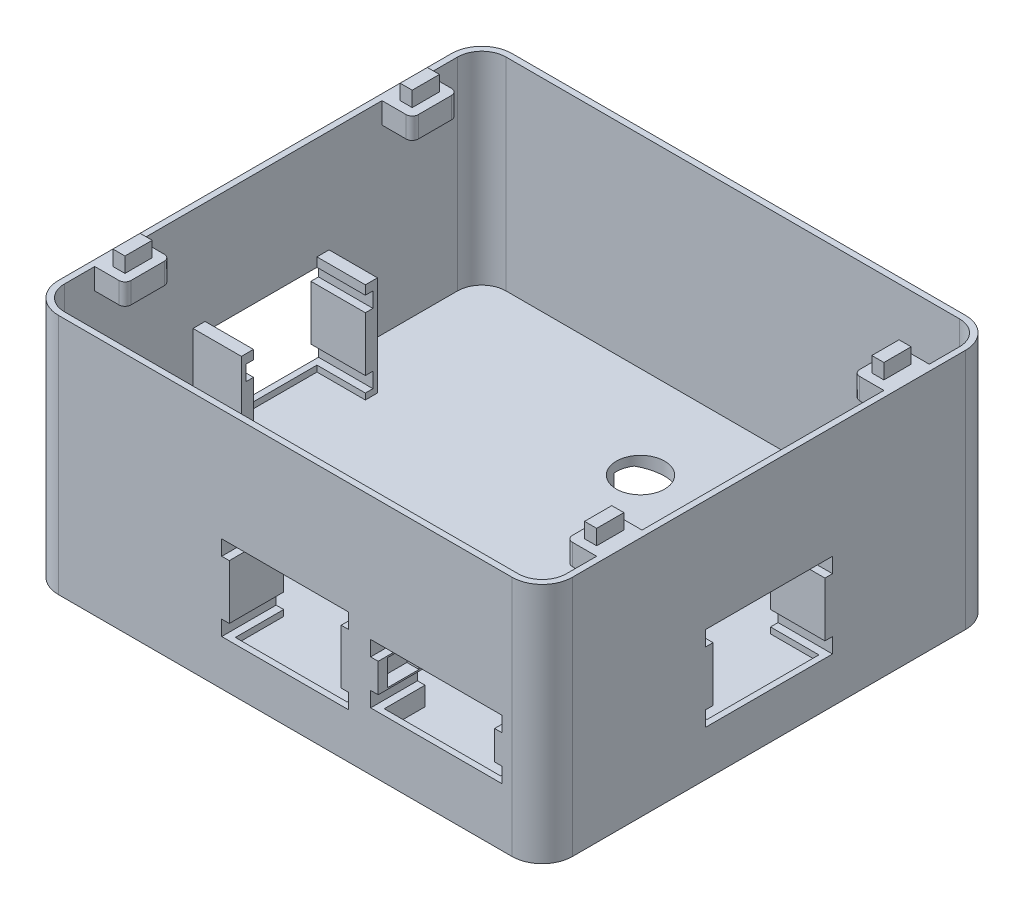
SolidWorks part; units mm, degrees
ref_plane "Front Plane" through (0, 0, 0) normal (0, 0, 1) x (1, 0, 0)
ref_plane "Top Plane" through (0, 0, 0) normal (0, 1, 0) x (1, 0, 0)
ref_plane "Right Plane" through (0, 0, 0) normal (1, 0, 0) x (0, 0, -1)
sketch "Sketch2" plane through (0, 0, 0) normal (0, 1, 0) x (1, 0, 0)
  line L1 (-85, 75) -> (85, 75)
  line L2 (-85, 75) -> (-85, -75)
  line L3 (-85, -75) -> (85, -75)
  line L4 (85, 75) -> (85, -75)
  line L5 (-85, 75) -> (85, -75) construction
  line L6 (-85, -75) -> (85, 75) construction
  point P0 (0, 0)
  dimension "D1" = 170
  dimension "D2" = 150
extrude "Boss-Extrude1" add sketch "Sketch2" along normal blind 80
fillet "Fillet1" radius 10 4 edges at (-85, 40, -75) (85, 40, -75) (85, 40, 75) (-85, 40, 75)
shell "Shell1" thickness 2
sketch "Sketch5" plane through (0, 0, 75) normal (0, 0, 1) x (1, 0, 0)
  line L1 (-18.5, 43) -> (18.5, 43)
  line L2 (-18.5, 43) -> (-18.5, 15)
  line L3 (-18.5, 15) -> (18.5, 15)
  line L4 (18.5, 43) -> (18.5, 15)
  line L5 (-18.5, 43) -> (-21, 43)
  line L6 (-21, 43) -> (-21, 38)
  line L7 (-21, 38) -> (-18.5, 38)
  line L8 (-18.5, 38) -> (-18.5, 43)
  line L9 (0, 43) -> (0, 15) construction
  line L10 (-18.5, 29) -> (18.5, 29) construction
  line L11 (-21, 20) -> (-18.5, 20)
  line L12 (-21, 15) -> (-21, 20)
  line L13 (-18.5, 15) -> (-21, 15)
  line L14 (-18.5, 20) -> (-18.5, 15)
  line L15 (21, 15) -> (21, 20)
  line L16 (18.5, 15) -> (21, 15)
  line L17 (18.5, 20) -> (18.5, 15)
  line L18 (21, 20) -> (18.5, 20)
  line L19 (21, 38) -> (18.5, 38)
  line L20 (21, 43) -> (21, 38)
  line L21 (18.5, 43) -> (21, 43)
  line L22 (18.5, 38) -> (18.5, 43)
  line L23 (-75, 13) -> (75, 13) construction
  point P4 (0, 15)
  dimension "D1" = 37
  dimension "D2" = 28
  dimension "D3" = 5
  dimension "D7" = 2.5
  dimension "D8" = 2
extrude "Cut-Extrude1" cut sketch "Sketch5" against normal up to surface (2 mm away) contours L1 L4 L3 L2 | L7 L8 L5 L6 | L12 L11 L14 L13 | L20 L19 L22 L21 | L15 L18 L17 L16 up to face at (0, 46.5, 73)
sketch "Sketch6" plane through (0, 0, 73) normal (0, 0, -1) x (-1, 0, 0)
  line L0 (18.5, 13) -> (22.5, 13)
  line L2 (-22.5, 46) -> (-22.5, 13)
  line L4 (21, 43) -> (18.5, 43)
  line L5 (21, 38) -> (21, 43)
  line L6 (18.5, 38) -> (21, 38)
  line L7 (18.5, 43) -> (18.5, 38)
  line L8 (21, 43) -> (18.5, 43)
  line L9 (21, 38) -> (21, 43)
  line L10 (18.5, 38) -> (21, 38)
  line L12 (18.5, 43) -> (-18.5, 43)
  line L13 (-18.5, 43) -> (-18.5, 15)
  line L14 (-18.5, 15) -> (18.5, 15)
  line L15 (18.5, 15) -> (18.5, 43)
  line L17 (-18.5, 46) -> (-18.5, 43)
  line L19 (18.5, 13) -> (18.5, 15)
  line L20 (-21, 38) -> (-18.5, 38)
  line L21 (-18.5, 38) -> (-18.5, 43)
  line L22 (-18.5, 43) -> (-21, 43)
  line L23 (-21, 43) -> (-21, 38)
  line L24 (-21, 38) -> (-18.5, 38)
  line L26 (-18.5, 43) -> (-21, 43)
  line L27 (-21, 43) -> (-21, 38)
  line L28 (-21, 20) -> (-21, 15)
  line L29 (-18.5, 20) -> (-21, 20)
  line L30 (-18.5, 15) -> (-18.5, 20)
  line L31 (-21, 15) -> (-18.5, 15)
  line L32 (-21, 20) -> (-21, 15)
  line L33 (-18.5, 20) -> (-21, 20)
  line L35 (-21, 15) -> (-18.5, 15)
  line L36 (21, 20) -> (18.5, 20)
  line L37 (18.5, 20) -> (18.5, 15)
  line L38 (18.5, 15) -> (21, 15)
  line L39 (21, 15) -> (21, 20)
  line L40 (21, 20) -> (18.5, 20)
  line L42 (18.5, 15) -> (21, 15)
  line L43 (21, 15) -> (21, 20)
  line L44 (22.5, 46) -> (22.5, 13)
  line L45 (-18.5, 13) -> (-22.5, 13)
  line L46 (-18.5, 38) -> (-18.5, 20)
  line L47 (18.5, 43) -> (18.5, 46)
  line L48 (18.5, 20) -> (18.5, 38)
  line L49 (-18.5, 15) -> (-18.5, 13)
  line L50 (22.5, 46) -> (18.5, 46)
  line L51 (-22.5, 46) -> (-18.5, 46)
  line L54 (21, 43) -> (-21, 43) construction
  line L55 (75, 13) -> (-75, 13) construction
  dimension "D6" = 3
  dimension "D7" = 4
  dimension "D8" = 4
  dimension "D1" = 0
  dimension "D2" = 0
  dimension "D3" = 0
  dimension "D4" = 0
  dimension "D5" = 0
extrude "Boss-Extrude2" add sketch "Sketch6" along normal blind 16
sketch "Sketch7" plane through (85, 0, 0) normal (1, 0, 0) x (0, 0, -1)
  line L0 (-65, 13) -> (65, 13) construction
  line L1 (-18.5, 43) -> (18.5, 43)
  line L2 (-18.5, 43) -> (-18.5, 15)
  line L3 (-18.5, 15) -> (18.5, 15)
  line L4 (18.5, 43) -> (18.5, 15)
  line L5 (-18.5, 43) -> (-21, 43)
  line L6 (-21, 43) -> (-21, 38)
  line L7 (-21, 38) -> (-18.5, 38)
  line L8 (-18.5, 38) -> (-18.5, 43)
  line L9 (0, 43) -> (0, 15) construction
  line L10 (-18.5, 29) -> (18.5, 29) construction
  line L11 (-21, 20) -> (-18.5, 20)
  line L12 (-21, 15) -> (-21, 20)
  line L13 (-18.5, 15) -> (-21, 15)
  line L14 (-18.5, 20) -> (-18.5, 15)
  line L15 (21, 15) -> (21, 20)
  line L16 (18.5, 15) -> (21, 15)
  line L17 (18.5, 20) -> (18.5, 15)
  line L18 (21, 20) -> (18.5, 20)
  line L19 (21, 38) -> (18.5, 38)
  line L20 (21, 43) -> (21, 38)
  line L21 (18.5, 43) -> (21, 43)
  line L22 (18.5, 38) -> (18.5, 43)
  dimension "D1" = 37
  dimension "D2" = 28
  dimension "D3" = 5
  dimension "D7" = 2.5
  dimension "D8" = 2
extrude "Cut-Extrude2" cut sketch "Sketch7" against normal blind 2 contours L1 L4 L3 L2 | L7 L8 L5 L6 | L12 L11 L14 L13 | L20 L19 L22 L21 | L15 L18 L17 L16
sketch "Sketch8" plane through (83, 0, 0) normal (-1, 0, 0) x (0, 0, 1)
  line L0 (65, 13) -> (-65, 13) construction
  line L1 (-22.5, 46) -> (-18.5, 46)
  line L2 (-22.5, 46) -> (-22.5, 13)
  line L3 (-22.5, 13) -> (-18.5, 13)
  line L4 (21, 43) -> (18.5, 43)
  line L5 (21, 38) -> (21, 43)
  line L6 (18.5, 38) -> (21, 38)
  line L7 (18.5, 43) -> (18.5, 38)
  line L8 (21, 43) -> (18.5, 43)
  line L9 (21, 38) -> (21, 43)
  line L10 (18.5, 38) -> (21, 38)
  line L20 (-21, 38) -> (-18.5, 38)
  line L21 (-18.5, 38) -> (-18.5, 43)
  line L22 (-18.5, 43) -> (-21, 43)
  line L23 (-21, 43) -> (-21, 38)
  line L24 (-21, 38) -> (-18.5, 38)
  line L26 (-18.5, 43) -> (-21, 43)
  line L27 (-21, 43) -> (-21, 38)
  line L28 (-21, 20) -> (-21, 15)
  line L29 (-18.5, 20) -> (-21, 20)
  line L30 (-18.5, 15) -> (-18.5, 20)
  line L31 (-21, 15) -> (-18.5, 15)
  line L32 (-21, 20) -> (-21, 15)
  line L33 (-18.5, 20) -> (-21, 20)
  line L35 (-21, 15) -> (-18.5, 15)
  line L36 (21, 20) -> (18.5, 20)
  line L37 (18.5, 20) -> (18.5, 15)
  line L38 (18.5, 15) -> (21, 15)
  line L39 (21, 15) -> (21, 20)
  line L40 (21, 20) -> (18.5, 20)
  line L42 (18.5, 15) -> (21, 15)
  line L43 (21, 15) -> (21, 20)
  line L44 (-18.5, 46) -> (-18.5, 43)
  line L46 (-18.5, 38) -> (-18.5, 20) construction
  line L47 (21, 43) -> (-21, 43) construction
  line L48 (-18.5, 38) -> (-18.5, 20)
  line L49 (-18.5, 15) -> (-18.5, 13)
  line L50 (18.5, 38) -> (18.5, 20) construction
  line L51 (18.5, 46) -> (22.5, 46)
  line L52 (18.5, 46) -> (18.5, 43)
  line L53 (18.5, 13) -> (22.5, 13)
  line L54 (22.5, 46) -> (22.5, 13)
  line L55 (18.5, 38) -> (18.5, 20)
  line L56 (18.5, 15) -> (18.5, 13)
  dimension "D6" = 4
  dimension "D7" = 4
  dimension "D2" = 3
  dimension "D1" = 0
  dimension "D3" = 0
  dimension "D4" = 0
  dimension "D5" = 0
extrude "Boss-Extrude3" add sketch "Sketch8" along normal blind 16
sketch "Sketch10" plane through (-85, 0, 0) normal (-1, 0, 0) x (0, 0, 1)
  line L1 (-18.5, 43) -> (18.5, 43)
  line L2 (-18.5, 43) -> (-18.5, 15)
  line L3 (-18.5, 15) -> (18.5, 15)
  line L4 (18.5, 43) -> (18.5, 15)
  line L5 (-18.5, 43) -> (-21, 43)
  line L6 (-21, 43) -> (-21, 38)
  line L7 (-21, 38) -> (-18.5, 38)
  line L8 (-18.5, 38) -> (-18.5, 43)
  line L9 (0, 43) -> (0, 15) construction
  line L10 (-18.5, 29) -> (18.5, 29) construction
  line L11 (-21, 20) -> (-18.5, 20)
  line L12 (-21, 15) -> (-21, 20)
  line L13 (-18.5, 15) -> (-21, 15)
  line L14 (-18.5, 20) -> (-18.5, 15)
  line L15 (21, 15) -> (21, 20)
  line L16 (18.5, 15) -> (21, 15)
  line L17 (18.5, 20) -> (18.5, 15)
  line L18 (21, 20) -> (18.5, 20)
  line L19 (21, 38) -> (18.5, 38)
  line L20 (21, 43) -> (21, 38)
  line L21 (18.5, 43) -> (21, 43)
  line L22 (18.5, 38) -> (18.5, 43)
  line L23 (-65, 13) -> (65, 13) construction
  dimension "D1" = 37
  dimension "D2" = 28
  dimension "D3" = 5
  dimension "D7" = 2.5
  dimension "D8" = 2
extrude "Cut-Extrude4" cut sketch "Sketch10" against normal blind 2 contours L1 L4 L3 L2 | L7 L8 L5 L6 | L12 L11 L14 L13 | L20 L19 L22 L21 | L15 L18 L17 L16
sketch "Sketch11" plane through (-83, 0, 0) normal (1, 0, 0) x (0, 0, -1)
  line L1 (-18.5, 38) -> (-18.5, 20) construction
  line L2 (-18.5, 46) -> (-22.5, 46)
  line L3 (-18.5, 46) -> (-18.5, 43)
  line L4 (21, 43) -> (18.5, 43)
  line L5 (21, 38) -> (21, 43)
  line L6 (18.5, 38) -> (21, 38)
  line L7 (18.5, 43) -> (18.5, 38)
  line L8 (21, 43) -> (18.5, 43)
  line L9 (21, 38) -> (21, 43)
  line L10 (18.5, 38) -> (21, 38)
  line L20 (-21, 38) -> (-18.5, 38)
  line L21 (-18.5, 38) -> (-18.5, 43)
  line L22 (-18.5, 43) -> (-21, 43)
  line L23 (-21, 43) -> (-21, 38)
  line L24 (-21, 38) -> (-18.5, 38)
  line L26 (-18.5, 43) -> (-21, 43)
  line L27 (-21, 43) -> (-21, 38)
  line L28 (-21, 20) -> (-21, 15)
  line L29 (-18.5, 20) -> (-21, 20)
  line L30 (-18.5, 15) -> (-18.5, 20)
  line L31 (-21, 15) -> (-18.5, 15)
  line L32 (-21, 20) -> (-21, 15)
  line L33 (-18.5, 20) -> (-21, 20)
  line L35 (-21, 15) -> (-18.5, 15)
  line L36 (21, 20) -> (18.5, 20)
  line L37 (18.5, 20) -> (18.5, 15)
  line L38 (18.5, 15) -> (21, 15)
  line L39 (21, 15) -> (21, 20)
  line L40 (21, 20) -> (18.5, 20)
  line L42 (18.5, 15) -> (21, 15)
  line L43 (21, 15) -> (21, 20)
  line L44 (-18.5, 13) -> (-22.5, 13)
  line L45 (-22.5, 46) -> (-22.5, 13)
  line L46 (65, 13) -> (-65, 13) construction
  line L47 (21, 43) -> (-21, 43) construction
  line L48 (-18.5, 38) -> (-18.5, 20)
  line L49 (-18.5, 15) -> (-18.5, 13)
  line L50 (18.5, 38) -> (18.5, 20) construction
  line L51 (18.5, 46) -> (22.5, 46)
  line L52 (18.5, 46) -> (18.5, 43)
  line L53 (18.5, 13) -> (22.5, 13)
  line L54 (22.5, 46) -> (22.5, 13)
  line L55 (18.5, 38) -> (18.5, 20)
  line L56 (18.5, 15) -> (18.5, 13)
  dimension "D2" = 4
  dimension "D6" = 3
  dimension "D7" = 4
  dimension "D1" = 0
  dimension "D3" = 0
  dimension "D4" = 0
  dimension "D5" = 0
extrude "Boss-Extrude4" add sketch "Sketch11" along normal blind 16
sketch "Sketch13" plane through (0, 0, 75) normal (0, 0, 1) x (1, 0, 0)
  line L0 (-18.5, 29) -> (18.5, 29) construction
  line L1 (-18.5, 29) -> (18.5, 29) construction
  line L2 (30.75, 38.8) -> (28.25, 38.8)
  line L3 (30.75, 38.8) -> (69.25, 38.8)
  line L4 (30.75, 38.8) -> (30.75, 19.2)
  line L5 (30.75, 19.2) -> (69.25, 19.2)
  line L6 (69.25, 38.8) -> (69.25, 19.2)
  line L7 (28.25, 38.8) -> (28.25, 33.8)
  line L8 (28.25, 33.8) -> (30.75, 33.8)
  line L9 (30.75, 38.8) -> (30.75, 33.8)
  line L10 (50, 38.8) -> (50, 19.2) construction
  line L11 (30.75, 19.2) -> (28.25, 19.2)
  line L12 (28.25, 19.2) -> (28.25, 24.2)
  line L13 (28.25, 24.2) -> (30.75, 24.2)
  line L14 (30.75, 19.2) -> (30.75, 24.2)
  line L15 (69.25, 19.2) -> (69.25, 24.2)
  line L16 (71.75, 24.2) -> (69.25, 24.2)
  line L17 (71.75, 19.2) -> (71.75, 24.2)
  line L18 (69.25, 19.2) -> (71.75, 19.2)
  line L19 (69.25, 38.8) -> (71.75, 38.8)
  line L20 (71.75, 38.8) -> (71.75, 33.8)
  line L21 (71.75, 33.8) -> (69.25, 33.8)
  line L22 (69.25, 38.8) -> (69.25, 33.8)
  point P6 (30.75, 29)
  point P7 (50, 19.2)
  dimension "D1" = 19.6
  dimension "D2" = 38.5
  dimension "D3" = 50
  dimension "D4" = 5
  dimension "D8" = 2.5
extrude "Cut-Extrude5" cut sketch "Sketch13" against normal up to surface (2 mm away) contours L3 L6 L5 L4 | L7 L8 L9 L2 | L12 L13 L14 L11 | L17 L16 L15 L18 | L20 L21 L22 L19 up to face at (0, 40.1667, 73)
sketch "Sketch14" plane through (0, 0, 73) normal (0, 0, -1) x (-1, 0, 0)
  line L0 (-22.5, 13) -> (-75, 13) construction
  line L1 (-69.25, 41.8) -> (-73.25, 41.8)
  line L2 (-69.25, 41.8) -> (-69.25, 38.8)
  line L3 (-69.25, 13) -> (-73.25, 13)
  line L6 (-73.25, 41.8) -> (-73.25, 13)
  line L12 (-28.25, 38.8) -> (-30.75, 38.8)
  line L13 (-28.25, 33.8) -> (-28.25, 38.8)
  line L14 (-30.75, 33.8) -> (-28.25, 33.8)
  line L15 (-30.75, 38.8) -> (-30.75, 33.8)
  line L16 (-28.25, 38.8) -> (-30.75, 38.8)
  line L17 (-28.25, 33.8) -> (-28.25, 38.8)
  line L18 (-30.75, 33.8) -> (-28.25, 33.8)
  line L20 (-69.25, 38.8) -> (-71.75, 38.8)
  line L21 (-71.75, 38.8) -> (-71.75, 33.8)
  line L22 (-71.75, 33.8) -> (-69.25, 33.8)
  line L23 (-69.25, 33.8) -> (-69.25, 38.8)
  line L24 (-69.25, 38.8) -> (-71.75, 38.8)
  line L25 (-71.75, 38.8) -> (-71.75, 33.8)
  line L26 (-71.75, 33.8) -> (-69.25, 33.8)
  line L28 (-69.25, 19.2) -> (-69.25, 24.2)
  line L29 (-69.25, 24.2) -> (-71.75, 24.2)
  line L30 (-71.75, 24.2) -> (-71.75, 19.2)
  line L31 (-71.75, 19.2) -> (-69.25, 19.2)
  line L33 (-69.25, 24.2) -> (-71.75, 24.2)
  line L34 (-71.75, 24.2) -> (-71.75, 19.2)
  line L35 (-71.75, 19.2) -> (-69.25, 19.2)
  line L36 (-28.25, 19.2) -> (-28.25, 24.2)
  line L37 (-28.25, 24.2) -> (-30.75, 24.2)
  line L38 (-30.75, 24.2) -> (-30.75, 19.2)
  line L39 (-30.75, 19.2) -> (-28.25, 19.2)
  line L40 (-28.25, 19.2) -> (-28.25, 24.2)
  line L41 (-28.25, 24.2) -> (-30.75, 24.2)
  line L43 (-30.75, 19.2) -> (-28.25, 19.2)
  line L44 (-28.25, 38.8) -> (-71.75, 38.8) construction
  line L45 (-30.75, 41.8) -> (-26.75, 41.8)
  line L46 (-30.75, 41.8) -> (-30.75, 38.8)
  line L47 (-30.75, 13) -> (-26.75, 13)
  line L48 (-26.75, 41.8) -> (-26.75, 13)
  line L49 (-69.25, 33.8) -> (-69.25, 24.2) construction
  line L50 (-30.75, 33.8) -> (-30.75, 24.2) construction
  line L51 (-69.25, 33.8) -> (-69.25, 24.2)
  line L52 (-69.25, 19.2) -> (-69.25, 13)
  line L53 (-30.75, 33.8) -> (-30.75, 24.2)
  line L54 (-30.75, 19.2) -> (-30.75, 13)
  dimension "D1" = 3
  dimension "D6" = 4
  dimension "D7" = 4
  dimension "D2" = 0
  dimension "D3" = 0
  dimension "D4" = 0
  dimension "D5" = 0
extrude "Boss-Extrude5" add sketch "Sketch14" along normal blind 13.5
sketch "Sketch15" plane through (26.75, 0, 0) normal (-1, 0, 0) x (0, 0, 1)
  line L4 (59.5, 13) -> (59.5, 41.8) construction
  line L5 (73, 13) -> (73, 41.8) construction
  line L6 (59.5, 41.8) -> (59.5, 13) construction
  line L7 (59.5, 33.8) -> (75, 33.8) construction
  line L8 (59.5, 24.2) -> (75, 24.2) construction
  line L12 (72, 24.7) -> (72, 33.3)
  line L13 (72, 33.3) -> (61.5, 33.3)
  line L14 (61.5, 33.3) -> (61.5, 24.7)
  line L15 (61.5, 24.7) -> (72, 24.7)
  dimension "D1" = 2
  dimension "D2" = 1
  dimension "D3" = 0.5
  dimension "D4" = 0.5
extrude "Cut-Extrude6" cut sketch "Sketch15" against normal up to surface (4 mm away) up to face at (30.75, 29, 67.25)
sketch "Sketch18" plane through (0, 0, 0) normal (1, 0, 0) x (0, 0, -1)
  line L0 (0, 0) -> (0, 10) construction
  line L2 (-22.5, 13) -> (-65, 13) construction
  line L3 (-42.5, 0) -> (-70, 0)
  line L4 (-70, 0) -> (-47.5, 10)
  line L5 (-47.5, 10) -> (-42.5, 10)
  line L6 (-42.5, 10) -> (-42.5, 0)
  line L7 (65, 0) -> (-65, 0) construction
  dimension "D1" = 3
  dimension "D2" = 70
  dimension "D3" = 5
  dimension "D4" = 42.5
revolve "Cut-Revolve1" cut sketch "Sketch18" angle 360 about L0
sketch "Sketch20" plane through (0, 0, 0) normal (0, -1, 0) x (1, 0, 0)
  circle A0 centre (0, -42.5) radius 8
  circle A1 centre (0, 0) radius 42.5 construction
  circle A2 centre (0, 0) radius 42.5 construction
  dimension "D1" = 16
extrude "Cut-Extrude8" cut sketch "Sketch20" against normal up to surface (13 mm away) up to face at (10, 13, 26.25)
sketch "Sketch22" plane through (0, 0, 0) normal (0, -1, 0) x (1, 0, 0)
  line L0 (-85, 65) -> (85, 65) construction
  line L1 (-82.0711, 72.0711) -> (-67.9289, 57.9289) construction
  line L2 (44, 0) -> (-44, 0) construction
  line L3 (0, -44) -> (0, 44) construction
  circle A0 centre (-67.9289, 57.9289) radius 3
  arc A5 (-75, 75) -> (-85, 65) centre (-75, 65) ccw construction
  circle A6 centre (-67.9289, -57.9289) radius 3
  circle A7 centre (67.9289, -57.9289) radius 3
  circle A8 centre (67.9289, 57.9289) radius 3
  dimension "D3" = 6
  dimension "D1" = 45
  dimension "D2" = 20
extrude "Cut-Extrude9" cut sketch "Sketch22" against normal blind 5
sketch "Sketch23" plane through (0, 13, 0) normal (0, 1, 0) x (1, 0, 0)
  line L0 (-83, 65) -> (-83, 22.5) construction
  line L1 (-83, 55) -> (-73, 55)
  line L2 (-83, 55) -> (-83, 40)
  line L3 (-83, 40) -> (-73, 40)
  line L4 (-73, 55) -> (-73, 40)
  dimension "D1" = 10
  dimension "D2" = 15
  dimension "D3" = 40
extrude "Boss-Extrude6" add sketch "Sketch23" along normal up to surface (7 mm away) from offset 60 up to face at (0, 80, 0)
sketch "Sketch24" plane through (0, 80, 0) normal (0, 1, 0) x (1, 0, 0)
  line L8 (-76, 52) -> (-80, 52)
  line L9 (-76, 43) -> (-76, 52)
  line L10 (-80, 43) -> (-76, 43)
  line L11 (-80, 52) -> (-80, 43)
  line L12 (-76, 52) -> (-80, 52)
  line L13 (-76, 43) -> (-76, 52)
  line L14 (-80, 43) -> (-76, 43)
  line L15 (-80, 52) -> (-80, 43)
  dimension "D1" = 3
extrude "Cut-Extrude10" cut sketch "Sketch24" against normal blind 5
mirror "Mirror1" about plane through (0, 0, 0) normal (1, 0, 0) of "Boss-Extrude6", "Cut-Extrude10" second plane through (0, 0, 0) second plane normal (0, 0, 1)
fillet "Fillet2" radius 2 8 edges at (-73, 76.5, -40) (-73, 76.5, -55) (-73, 76.5, 40) (-73, 76.5, 55) (73, 76.5, -40) (73, 76.5, -55) (73, 76.5, 40) (73, 76.5, 55)
sketch "Sketch25" plane through (0, 0, 75) normal (0, 0, 1) x (1, 0, 0)
  line L0 (-69, 74) -> (-69, 19)
  line L1 (-69, 19) -> (-33.5, 19)
  line L2 (-33.5, 19) -> (-33.5, 74)
  line L3 (-27.5, 49) -> (27.5, 49)
  line L4 (27.5, 49) -> (27.5, 74)
  line L5 (27.5, 74) -> (-27.5, 74)
  line L6 (-33.5, 74) -> (-69, 74)
  line L7 (33.5, 49) -> (69, 49)
  line L8 (69, 49) -> (69, 74)
  line L9 (69, 74) -> (33.5, 74)
  line L10 (33.5, 74) -> (33.5, 49)
  line L11 (-27.5, 74) -> (-27.5, 49)
  line L12 (-75, 80) -> (75, 80) construction
  line L13 (-21, 43) -> (21, 43) construction
  line L14 (75, 0) -> (75, 80) construction
  line L15 (-75, 80) -> (-75, 0) construction
  line L17 (-75, 13) -> (-22.5, 13) construction
  point P4 (0, 49)
  dimension "D1" = 6
  dimension "D2" = 6
  dimension "D3" = 6
  dimension "D4" = 6
  dimension "D5" = 6
  dimension "D6" = 6
  dimension "D7" = 6
  dimension "D8" = 55
sketch "Sketch26" plane through (83, 0, 0) normal (-1, 0, 0) x (0, 0, 1)
  line L0 (-37, 19) -> (-25.5, 19)
  line L1 (-25.5, 19) -> (-25.5, 74)
  line L2 (-25.5, 74) -> (-37, 74)
  line L3 (-37, 74) -> (-37, 19)
  line L4 (-19.5, 74) -> (-19.5, 52)
  line L5 (-19.5, 52) -> (19.5, 52)
  line L6 (19.5, 52) -> (19.5, 74)
  line L7 (19.5, 74) -> (-19.5, 74)
  line L8 (25.5, 74) -> (25.5, 19)
  line L9 (25.5, 19) -> (37, 19)
  line L10 (37, 19) -> (37, 74)
  line L11 (37, 74) -> (25.5, 74)
  line L12 (-22.5, 13) -> (-65, 13) construction
  line L15 (-22.5, 46) -> (-22.5, 13) construction
  line L18 (-18.5, 46) -> (-22.5, 46) construction
  line L19 (40, 80) -> (-40, 80) construction
  line L20 (-40, 80) -> (-40, 73) construction
  line L21 (40, 80) -> (40, 73) construction
  line L23 (-59, 67) -> (-43, 67)
  line L24 (-59, 67) -> (-59, 19)
  line L25 (-59, 19) -> (-43, 19)
  line L26 (-43, 67) -> (-43, 19)
  line L27 (43, 67) -> (59, 67)
  line L28 (43, 67) -> (43, 19)
  line L29 (43, 19) -> (59, 19)
  line L30 (59, 67) -> (59, 19)
  line L31 (-65, 13) -> (-65, 80) construction
  line L32 (55, 73) -> (40, 73) construction
  line L33 (65, 80) -> (65, 13) construction
  line L34 (-55, 73) -> (-40, 73) construction
  point P16 (0, 52)
  dimension "D1" = 6
  dimension "D2" = 6
  dimension "D3" = 6
  dimension "D4" = 6
  dimension "D5" = 3
  dimension "D6" = 3
  dimension "D7" = 3
  dimension "D8" = 6
  dimension "D9" = 6
  dimension "D10" = 6
  dimension "D11" = 6
  dimension "D12" = 6
  dimension "D13" = 6
  dimension "D14" = 6
sketch "Sketch29" plane through (-85, 0, 0) normal (-1, 0, 0) x (0, 0, 1)
  line L4 (25.5, 74) -> (25.5, 19)
  line L5 (25.5, 19) -> (37, 19)
  line L6 (37, 19) -> (37, 74)
  line L7 (37, 74) -> (25.5, 74)
  line L8 (25.5, 74) -> (25.5, 19)
  line L9 (25.5, 19) -> (37, 19)
  line L10 (37, 19) -> (37, 74)
  line L11 (37, 74) -> (25.5, 74)
  line L12 (-19.5, 74) -> (-19.5, 52)
  line L13 (-19.5, 52) -> (19.5, 52)
  line L14 (19.5, 52) -> (19.5, 74)
  line L15 (19.5, 74) -> (-19.5, 74)
  line L16 (-19.5, 74) -> (-19.5, 52)
  line L17 (-19.5, 52) -> (19.5, 52)
  line L18 (19.5, 52) -> (19.5, 74)
  line L19 (19.5, 74) -> (-19.5, 74)
  line L20 (-37, 19) -> (-25.5, 19)
  line L21 (-25.5, 19) -> (-25.5, 74)
  line L22 (-25.5, 74) -> (-37, 74)
  line L23 (-37, 74) -> (-37, 19)
  line L24 (-37, 19) -> (-25.5, 19)
  line L25 (-25.5, 19) -> (-25.5, 74)
  line L26 (-25.5, 74) -> (-37, 74)
  line L27 (-37, 74) -> (-37, 19)
  line L28 (-43, 67) -> (-59, 67)
  line L29 (-43, 19) -> (-43, 67)
  line L30 (-59, 19) -> (-43, 19)
  line L31 (-59, 67) -> (-59, 19)
  line L32 (-43, 67) -> (-59, 67)
  line L33 (-43, 19) -> (-43, 67)
  line L34 (-59, 19) -> (-43, 19)
  line L35 (-59, 67) -> (-59, 19)
  line L36 (59, 67) -> (43, 67)
  line L37 (43, 67) -> (43, 19)
  line L38 (43, 19) -> (59, 19)
  line L39 (59, 19) -> (59, 67)
  line L40 (59, 67) -> (43, 67)
  line L41 (43, 67) -> (43, 19)
  line L42 (43, 19) -> (59, 19)
  line L43 (59, 19) -> (59, 67)
  dimension "D1" = 0
  dimension "D2" = 0
  dimension "D3" = 0
  dimension "D4" = 0
  dimension "D5" = 0
sketch "Sketch27" plane through (0, 0, -75) normal (0, 0, -1) x (-1, 0, 0)
  line L0 (75, 0) -> (75, 80) construction
  line L1 (-69, 74) -> (-41, 74)
  line L2 (-69, 74) -> (-69, 19)
  line L3 (-69, 19) -> (-41, 19)
  line L4 (-41, 74) -> (-41, 19)
  line L5 (-35, 74) -> (35, 74)
  line L6 (-35, 74) -> (-35, 19)
  line L7 (-35, 19) -> (35, 19)
  line L8 (35, 74) -> (35, 19)
  line L9 (41, 74) -> (69, 74)
  line L10 (41, 74) -> (41, 19)
  line L11 (41, 19) -> (69, 19)
  line L12 (69, 74) -> (69, 19)
  line L13 (-75, 80) -> (-75, 0) construction
  line L14 (-75, 80) -> (75, 80) construction
  line L15 (-75, 13) -> (75, 13) construction
  point P20 (0, 19)
  dimension "D1" = 6
  dimension "D2" = 6
  dimension "D3" = 6
  dimension "D4" = 6
  dimension "D5" = 6
  dimension "D6" = 6
  dimension "D7" = 70
sketch "Sketch28" plane through (0, 0, 0) normal (0, -1, 0) x (1, 0, 0)
  arc A2 (10.9512, -41.4647) -> (-10.9512, -41.4647) centre (0, -42.5) ccw
  arc A3 (10.1172, -38.1824) -> (-10.1172, -38.1824) centre (0, -42.5) ccw
  arc A6 (7.4023, -38.8002) -> (-7.4023, -38.8002) centre (0, 0) ccw
  arc A7 (10.1172, -38.1824) -> (-10.1172, -38.1824) centre (0, 0) ccw
  dimension "D1" = 3
  dimension "D2" = 3
extrude "Cut-Extrude14" cut sketch "Sketch28" against normal up to surface (10 mm away) up to face at (0, 10, 0.2422)
sketch "Sketch30" plane through (0, 0, 0) normal (0, -1, 0) x (1, 0, 0)
  line L0 (12.0416, -72) -> (75, -72)
  line L1 (-12.0416, 72) -> (-75, 72)
  line L8 (-82, 65) -> (-82, -65)
  line L9 (-75, -72) -> (75, -72)
  line L10 (82, -65) -> (82, 65)
  line L11 (75, 72) -> (-75, 72)
  line L12 (-82, 65) -> (-82, -65)
  line L13 (-75, -72) -> (-12.0416, -72)
  line L14 (82, -65) -> (82, 65)
  line L15 (75, 72) -> (12.0416, 72)
  circle A2 centre (0, 0) radius 73
  arc A3 (12.0416, -72) -> (12.0416, 72) centre (0, 0) ccw
  circle A5 centre (67.9289, 57.9289) radius 6
  circle A6 centre (67.9289, 57.9289) radius 6
  arc A8 (-82, -65) -> (-75, -72) centre (-75, -65) ccw
  arc A9 (75, -72) -> (82, -65) centre (75, -65) ccw
  arc A10 (82, 65) -> (75, 72) centre (75, 65) ccw
  arc A11 (-75, 72) -> (-82, 65) centre (-75, 65) ccw
  arc A12 (-82, -65) -> (-75, -72) centre (-75, -65) ccw
  arc A13 (75, -72) -> (82, -65) centre (75, -65) ccw
  arc A14 (82, 65) -> (75, 72) centre (75, 65) ccw
  arc A15 (-75, 72) -> (-82, 65) centre (-75, 65) ccw
  circle A16 centre (67.9289, -57.9289) radius 6
  circle A17 centre (67.9289, -57.9289) radius 6
  arc A18 (-12.0416, 72) -> (-12.0416, -72) centre (0, 0) ccw
  circle A19 centre (-67.9289, -57.9289) radius 6
  circle A20 centre (-67.9289, -57.9289) radius 6
  circle A34 centre (-67.9289, 57.9289) radius 6
  circle A35 centre (-67.9289, 57.9289) radius 6
  dimension "D1" = 3
  dimension "D2" = 3
  dimension "D3" = 3
  dimension "D4" = 3
  dimension "D5" = 3
  dimension "D6" = 3
extrude "Cut-Extrude16" cut sketch "Sketch30" against normal offset from surface (10 mm away) 3 up to face at (0, 13, -34.5)
sketch "Sketch31" plane through (0, 75, 0) normal (0, 1, 0) x (1, 0, 0)
  line L4 (-76, 43) -> (-76, 52)
  line L5 (-76, 52) -> (-80, 52)
  line L6 (-80, 52) -> (-80, 43)
  line L7 (-80, 43) -> (-76, 43)
  line L8 (-76, 43) -> (-76, 52)
  line L9 (-76, 52) -> (-80, 52)
  line L10 (-80, 52) -> (-80, 43)
  line L11 (-80, 43) -> (-76, 43)
  line L12 (-76, -52) -> (-76, -43)
  line L13 (-76, -43) -> (-80, -43)
  line L14 (-80, -43) -> (-80, -52)
  line L15 (-80, -52) -> (-76, -52)
  line L16 (-76, -52) -> (-76, -43)
  line L17 (-76, -43) -> (-80, -43)
  line L18 (-80, -43) -> (-80, -52)
  line L19 (-80, -52) -> (-76, -52)
  line L20 (76, 52) -> (76, 43)
  line L21 (76, 43) -> (80, 43)
  line L22 (80, 43) -> (80, 52)
  line L23 (80, 52) -> (76, 52)
  line L24 (76, 52) -> (76, 43)
  line L25 (76, 43) -> (80, 43)
  line L26 (80, 43) -> (80, 52)
  line L27 (80, 52) -> (76, 52)
  line L28 (76, -43) -> (76, -52)
  line L29 (76, -52) -> (80, -52)
  line L30 (80, -52) -> (80, -43)
  line L31 (80, -43) -> (76, -43)
  line L32 (76, -43) -> (76, -52)
  line L33 (76, -52) -> (80, -52)
  line L34 (80, -52) -> (80, -43)
  line L35 (80, -43) -> (76, -43)
  dimension "D1" = 0
  dimension "D2" = 0
  dimension "D3" = 0
  dimension "D4" = 0
extrude "Boss-Extrude7" add sketch "Sketch31" along normal blind 10
